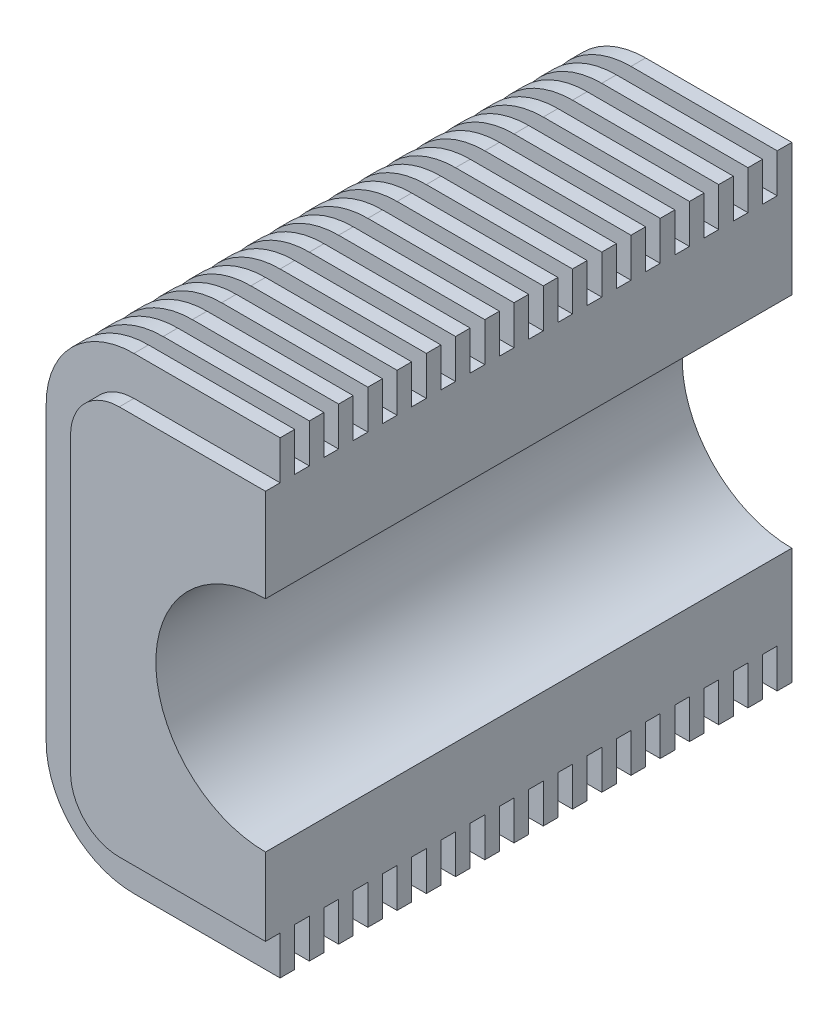
SolidWorks part; units mm, degrees
ref_plane "Płaszczyzna przednia" through (0, 0, 0) normal (0, 0, 1) x (1, 0, 0)
ref_plane "Płaszczyzna górna" through (0, 0, 0) normal (0, 1, 0) x (1, 0, 0)
ref_plane "Płaszczyzna prawa" through (0, 0, 0) normal (1, 0, 0) x (0, 0, -1)
sketch "Szkic1" plane through (0, 0, 0) normal (0, 0, 1) x (1, 0, 0)
  line L0 (0, 75) -> (-30, 75) construction
  line L1 (-40, 5) -> (-40, 65) construction
  line L2 (0, -5) -> (-30, -5) construction
  line L3 (0, 75) -> (-30, 75)
  line L4 (-40, 5) -> (-40, 65)
  line L5 (0, -5) -> (-30, -5)
  line L6 (0, -5) -> (0, 75)
  arc A0 (-30, 75) -> (-40, 65) centre (-30, 65) ccw construction
  arc A1 (-40, 5) -> (-30, -5) centre (-30, 5) ccw construction
  arc A2 (-30, 75) -> (-40, 65) centre (-30, 65) ccw
  arc A3 (-40, 5) -> (-30, -5) centre (-30, 5) ccw
extrude "Dodanie-wyciągnięcie1" add sketch "Szkic1" along normal blind 108
sketch "Szkic2" plane through (0, 0, 108) normal (0, 0, 1) x (1, 0, 0)
  circle A0 centre (0, 33.3858) radius 22.5 construction
  circle A1 centre (0, 33.3858) radius 22.5
extrude "Wytnij-wyciągnięcie1" cut sketch "Szkic2" against normal through all
sketch "Szkic3" plane through (0, 0, 0) normal (0, 0, -1) x (-1, 0, 0)
  line L0 (0, 75) -> (30, 75) construction
  line L1 (40, 65) -> (40, 5) construction
  line L2 (30, -5) -> (0, -5) construction
  line L3 (0, 75) -> (30, 75)
  line L4 (40, 65) -> (40, 5)
  line L5 (30, -5) -> (0, -5)
  line L6 (0, 83) -> (30, 83)
  line L7 (48, 65) -> (48, 5)
  line L8 (30, -13) -> (0, -13)
  line L9 (0, -13) -> (0, -5)
  line L10 (0, 75) -> (0, 83)
  arc A0 (40, 65) -> (30, 75) centre (30, 65) ccw construction
  arc A1 (30, -5) -> (40, 5) centre (30, 5) ccw construction
  arc A2 (40, 65) -> (30, 75) centre (30, 65) ccw
  arc A3 (30, -5) -> (40, 5) centre (30, 5) ccw
  arc A4 (48, 65) -> (30, 83) centre (30, 65) ccw
  arc A5 (30, -13) -> (48, 5) centre (30, 5) ccw
  dimension "D1" = 8
extrude "Dodanie-wyciągnięcie2" add sketch "Szkic3" against normal blind 3
pattern_linear "Szyk liniowy5" count 18 spacing 6 along (0, 0, 1) of "Dodanie-wyciągnięcie2"
